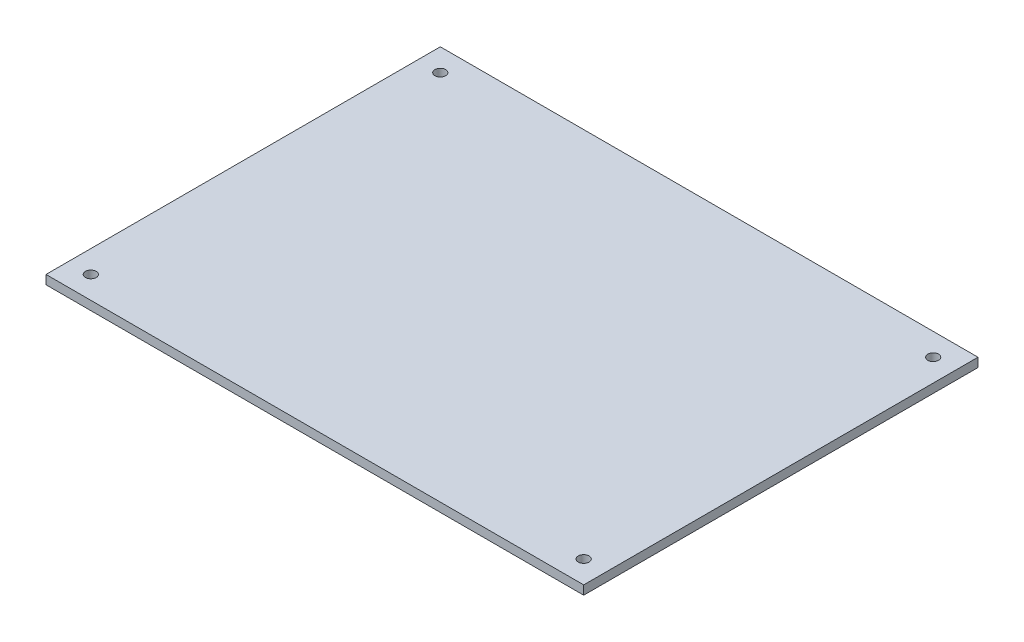
SolidWorks part; units mm, degrees
material "Maple"
ref_plane "Front Plane" through (0, 0, 0) normal (0, 0, 1) x (1, 0, 0)
ref_plane "Top Plane" through (0, 0, 0) normal (0, 1, 0) x (1, 0, 0)
ref_plane "Right Plane" through (0, 0, 0) normal (1, 0, 0) x (0, 0, -1)
sketch "Sketch1" plane through (0, 0, 0) normal (0, 1, 0) x (1, 0, 0)
  line L1 (-150, 110) -> (150, 110)
  line L2 (-150, 110) -> (-150, -110)
  line L3 (-150, -110) -> (150, -110)
  line L4 (150, 110) -> (150, -110)
  line L5 (-150, 110) -> (150, -110) construction
  line L6 (-150, -110) -> (150, 110) construction
  point P0 (0, 0)
  dimension "D1" = 300
  dimension "D2" = 220
extrude "Boss-Extrude1" add sketch "Sketch1" along normal blind 5
sketch "Sketch2" plane through (0, 0, 0) normal (0, -1, 0) x (1, 0, 0)
  line L0 (-150, 110) -> (40, -110) construction
  line L1 (150, -110) -> (-150, -110) construction
  line L2 (-150, -110) -> (-150, 110) construction
  circle A0 centre (-55, 0) radius 12.5
  point P6 (15.4985, -110)
  dimension "D1" = 25
  dimension "D2" = 190
extrude "Cut-Extrude1" cut sketch "Sketch2" against normal blind 1
hole_wizard "Ø6.0 (6) Diameter Hole1" positions "Sketch4" profile "Sketch3" hole size "Ø6.0" standard "ISO"
sketch "Sketch4" plane through (0, 0, 0) normal (0, -1, 0) x (-1, 0, 0)
  point P2 (137.5, -97.5)
  point P4 (137.5, 97.5)
  point P6 (-137.5, 97.5)
  point P8 (-137.5, -97.5)
sketch "Sketch3" plane through (-137.5, 0, 97.5) normal (1, 0, 0) x (0, 0, -1)
  line L0 (0, 0) -> (0, 11.8026)
  line L1 (0, 11.8026) -> (3, 10)
  line L2 (3, 10) -> (3, 0)
  line L5 (3, 0) -> (0, 0)
  line L10 (0, 11.8026) -> (-3, 10) construction
  line L11 (0, -6.35) -> (0, 107.95) construction
  dimension "Hole Dia." = 6
  dimension "Hole Depth" = 10
  dimension "Drill Angle" = 118
